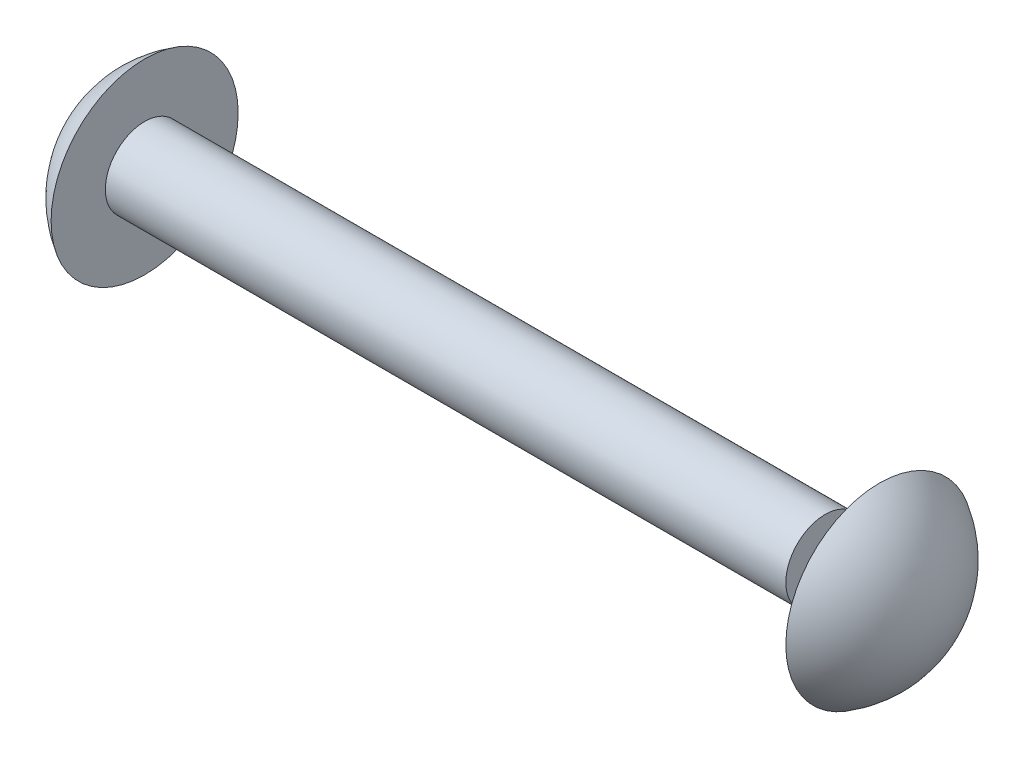
SolidWorks part; units mm, degrees
ref_plane "Front Plane" through (0, 0, 0) normal (1, 0, 0) x (0, 1, 0)
ref_plane "Top Plane" through (0, 0, 0) normal (0, 0, 1) x (0, 1, 0)
ref_plane "Right Plane" through (0, 0, 0) normal (0, 1, 0) x (-1, 0, 0)
sketch "Sketch2" plane through (0, 0, 0) normal (1, 0, 0) x (0, 1, 0)
  circle A0 centre (0, 0) radius 1.45
  dimension "D1" = 2.9
extrude "Boss-Extrude1" add sketch "Sketch2" along normal mid plane 25.1
sketch "Sketch3" plane through (0, 0, 0) normal (0, 0, 1) x (0, 1, 0)
  line L1 (1.45, 12.55) -> (-1.45, 12.55) construction
  line L2 (1.45, 12.55) -> (-1.45, 12.55) construction
  line L3 (0, 12.55) -> (0, 14.55)
  line L4 (3.45, 12.55) -> (0, 12.55)
  arc A0 (0, 14.55) -> (3.45, 12.55) centre (0, 10.5744) cw
  point P0 (0.7241, 5.6187)
  point P5 (0, 12.55)
  point P6 (0, 12.55)
  dimension "D1" = 3.45
  dimension "D2" = 2
revolve "Revolve1" add sketch "Sketch3" angle 360 about L3
ref_plane "Plane1" through (1, 0, 0) normal (1, 0, 0) x (0, 1, 0)
sketch "Sketch4" plane through (1, 0, 0) normal (1, 0, 0) x (0, 1, 0)
  line L0 (0, 0) -> (0, 0.8632) construction
pattern_circular "CirPattern3" count 2 every 180 about axis through (1, 0, 0) along (0, 0, 1) of bodies 102
